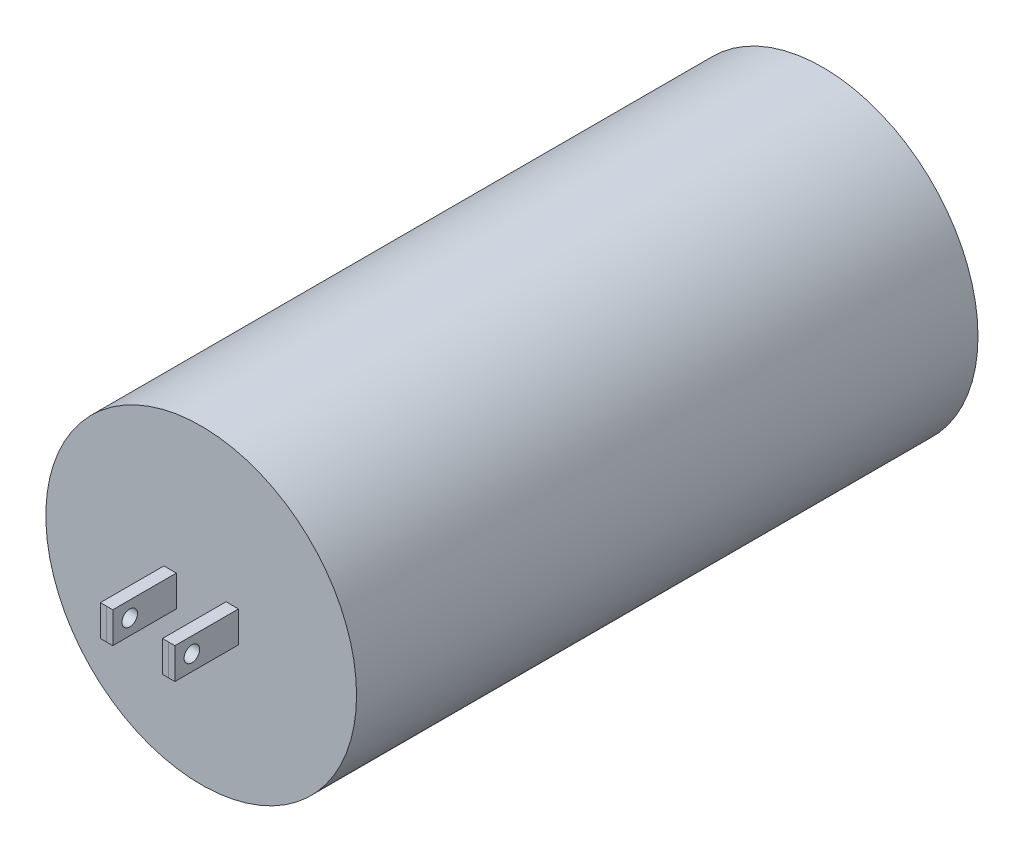
SolidWorks part; units mm, degrees
ref_plane "Front Plane" through (0, 0, 0) normal (0, 0, 1) x (1, 0, 0)
ref_plane "Top Plane" through (0, 0, 0) normal (0, 1, 0) x (1, 0, 0)
ref_plane "Right Plane" through (0, 0, 0) normal (1, 0, 0) x (0, 0, -1)
sketch "Sketch1" plane through (0, 0, 0) normal (0, 0, 1) x (1, 0, 0)
  circle A0 centre (0, 0) radius 50
extrude "Boss-Extrude1" add sketch "Sketch1" along normal blind 200
sketch "Sketch2" plane through (0, 0, 0) normal (0, 1, 0) x (1, 0, 0)
  line L0 (-50, -200) -> (50, -200) construction
  line L1 (-10, -200) -> (-12, -200)
  line L2 (-10, -200) -> (-10, -220.4632)
  line L3 (-10, -220.4632) -> (-12, -220.4632)
  line L4 (-12, -200) -> (-12, -220.4632)
  line L6 (10, -220.4632) -> (12, -220.4632)
  line L7 (12, -200) -> (12, -220.4632)
  line L8 (10, -200) -> (12, -200)
  line L9 (10, -200) -> (10, -220.4632)
  dimension "D1" = 38
  dimension "D2" = 2
extrude "Boss-Extrude2" add sketch "Sketch2" along normal mid plane 10
sketch "Sketch3" plane through (0, 0, 0) normal (1, 0, 0) x (0, 0, -1)
  circle A0 centre (-215, 0) radius 2.5
extrude "Cut-Extrude1" cut sketch "Sketch3" against normal mid plane 34
sketch "Sketch4" plane through (0, 0, 0) normal (0, 0, 1) x (1, 0, 0)
  line L0 (0, 0) -> (0, 2.499)
  line L1 (-10, -5) -> (-8, -5)
  line L2 (-10, -5) -> (-10, 5)
  line L3 (-10, 5) -> (-8, 5)
  line L4 (-8, -5) -> (-8, 5)
  line L5 (10, -5) -> (8, -5)
  line L6 (8, -5) -> (8, 5)
  line L7 (10, -5) -> (10, 5)
  line L8 (10, 5) -> (8, 5)
  dimension "D1" = 10
  dimension "D2" = 2
extrude "Boss-Extrude3" add sketch "Sketch4" along normal blind 20.46 from surface at 200 contours L1 L4 L3 L2 | L7 L8 L6 L5 starting at face at (11, 0, 200)
sketch "Sketch5" plane through (0, 0, 0) normal (1, 0, 0) x (0, 0, -1)
  circle A0 centre (-215, 0) radius 2.5
extrude "Cut-Extrude2" cut sketch "Sketch5" against normal mid plane 25
